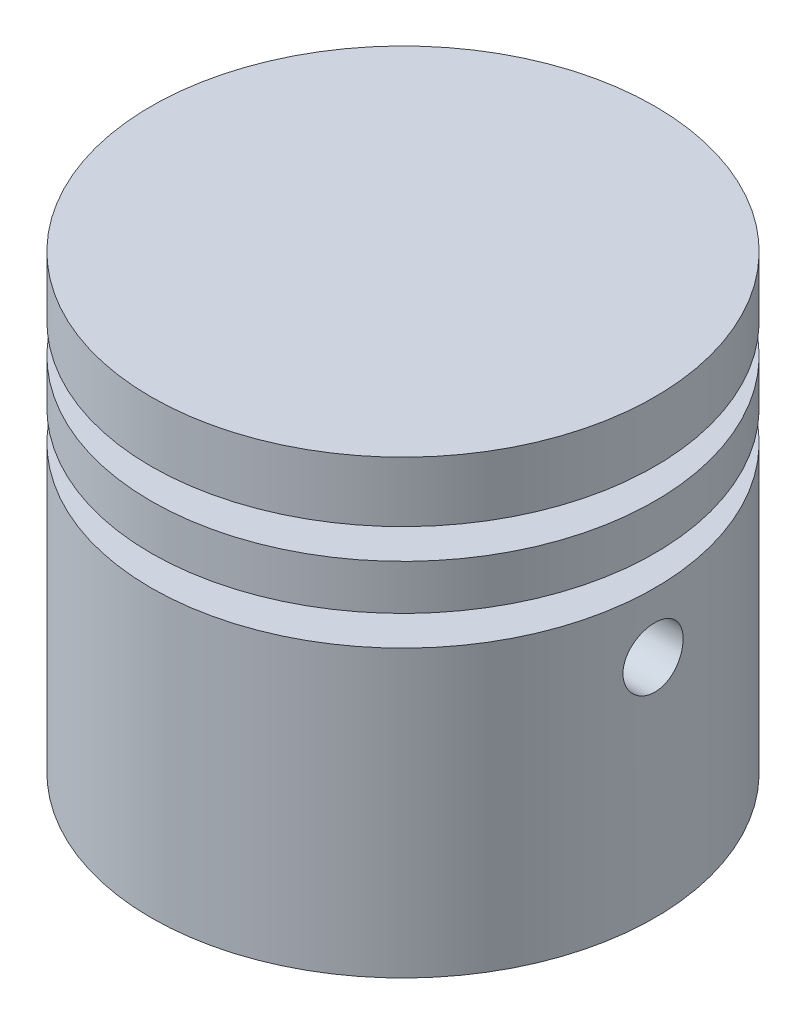
SolidWorks part; units mm, degrees
ref_plane "Front Plane" through (0, 0, 0) normal (0, 0, 1) x (1, 0, 0)
ref_plane "Top Plane" through (0, 0, 0) normal (0, 1, 0) x (1, 0, 0)
ref_plane "Right Plane" through (0, 0, 0) normal (1, 0, 0) x (0, 0, -1)
sketch "Sketch3" plane through (0, 0, 0) normal (0, 0, 1) x (1, 0, 0)
  line L0 (0, -381) -> (0, 381) construction
  line L1 (0, -381) -> (-254, -381) construction
  line L2 (-425.45, -381) -> (425.45, -381) construction
  line L3 (-425.45, 381) -> (-425.45, 279.4)
  line L4 (-425.45, 381) -> (0, 381)
  line L5 (-425.45, 279.4) -> (-336.55, 279.4)
  line L6 (-336.55, 279.4) -> (-336.55, 228.6)
  line L7 (-336.55, 228.6) -> (-425.45, 228.6)
  line L8 (-425.45, 228.6) -> (-425.45, 152.4)
  line L9 (-425.45, 152.4) -> (-336.55, 152.4)
  line L10 (-336.55, 152.4) -> (-336.55, 101.6)
  line L11 (-336.55, 101.6) -> (-425.45, 101.6)
  line L12 (-425.45, 101.6) -> (-425.45, -381)
  line L13 (-254, -381) -> (-254, -254) construction
  line L14 (-254, -254) -> (-381, -381)
  line L15 (-381, -381) -> (-425.45, -381)
  line L16 (-254, -254) -> (-254, 304.8)
  line L17 (-254, 304.8) -> (0, 304.8)
  line L18 (0, 304.8) -> (0, -381)
  line L19 (0, 381) -> (0, 304.8)
  point P4 (0, 0)
  point P9 (0, -381)
  dimension "D1" = 762
  dimension "D2" = 381
  dimension "D3" = 254
  dimension "D4" = 425.45
  dimension "D5" = 101.6
  dimension "D6" = 88.9
  dimension "D7" = 50.8
  dimension "D8" = 76.2
  dimension "D9" = 50.8
  dimension "D10" = 127
  dimension "D11" = 45
  dimension "D12" = 685.8
revolve "Revolve1" add sketch "Sketch3" angle 360 about L0
sketch "Sketch4" plane through (0, 0, 0) normal (1, 0, 0) x (0, 0, -1)
  line L0 (0, -381) -> (0, 0) construction
  line L1 (-425.45, -381) -> (425.45, -381) construction
  circle A0 centre (0, 0) radius 50.8
  dimension "D1" = 101.6
extrude "Cut-Extrude1" cut sketch "Sketch4" against normal through all both and the other way through all
